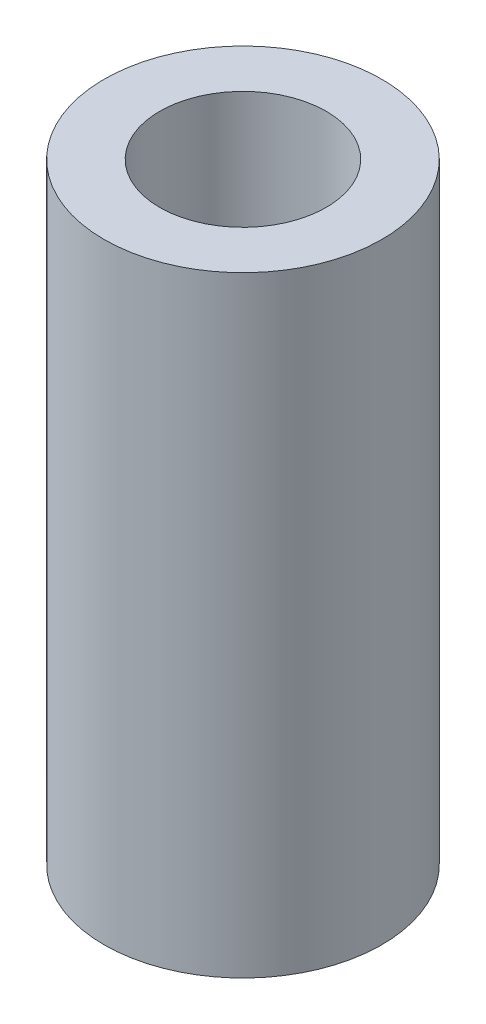
SolidWorks part; units mm, degrees
ref_plane "Спереди" through (0, 0, 0) normal (0, 0, 1) x (1, 0, 0)
ref_plane "Сверху" through (0, 0, 0) normal (0, 1, 0) x (1, 0, 0)
ref_plane "Справа" through (0, 0, 0) normal (1, 0, 0) x (0, 0, -1)
sketch "Эскиз1" plane through (0, 0, 0) normal (0, 1, 0) x (1, 0, 0)
  circle A0 centre (0, 0) radius 1.5
  circle A1 centre (0, 0) radius 2.5
extrude "Бобышка-Вытянуть1" add sketch "Эскиз1" along normal blind 11
